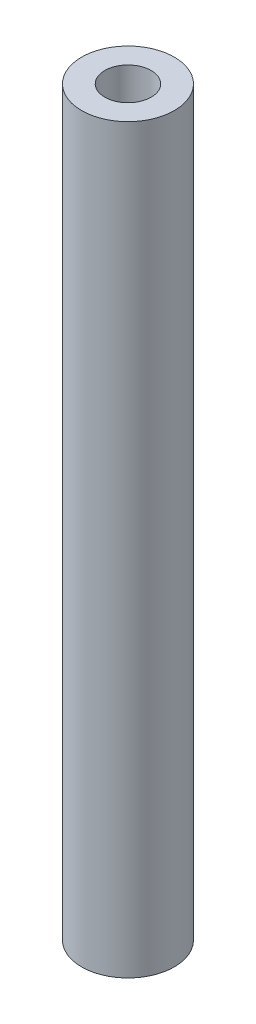
SolidWorks part; units mm, degrees
ref_plane "Front Plane" through (0, 0, 0) normal (0, 0, 1) x (1, 0, 0)
ref_plane "Top Plane" through (0, 0, 0) normal (0, 1, 0) x (1, 0, 0)
ref_plane "Right Plane" through (0, 0, 0) normal (1, 0, 0) x (0, 0, -1)
sketch "Sketch2" plane through (0, 0, 0) normal (0, 1, 0) x (1, 0, 0)
  circle A0 centre (0, 0) radius 2
  dimension "D1" = 4
extrude "Boss-Extrude1" add sketch "Sketch2" along normal blind 32
ref_plane "Plane1" through (0, 30, 0) normal (0, 1, 0) x (1, 0, 0)
sketch "Sketch4" plane through (0, 30, 0) normal (0, 1, 0) x (1, 0, 0)
  circle A0 centre (0, 0) radius 1.9
  circle A1 centre (0, 0) radius 2.2
  dimension "D1" = 3.8
sketch "Sketch11" plane through (0, 32, 0) normal (0, 1, 0) x (1, 0, 0)
  circle A0 centre (0, 0) radius 1
  dimension "D1" = 2
extrude "Cut-Extrude3" cut sketch "Sketch11" against normal blind 5
scale "Scale1" scale about origin uniform scaling yes scale factor 2
sketch "Sketch13" plane through (0, 30, 0) normal (0, 1, 0) x (1, 0, 0)
  circle A0 centre (0, 0) radius 4
